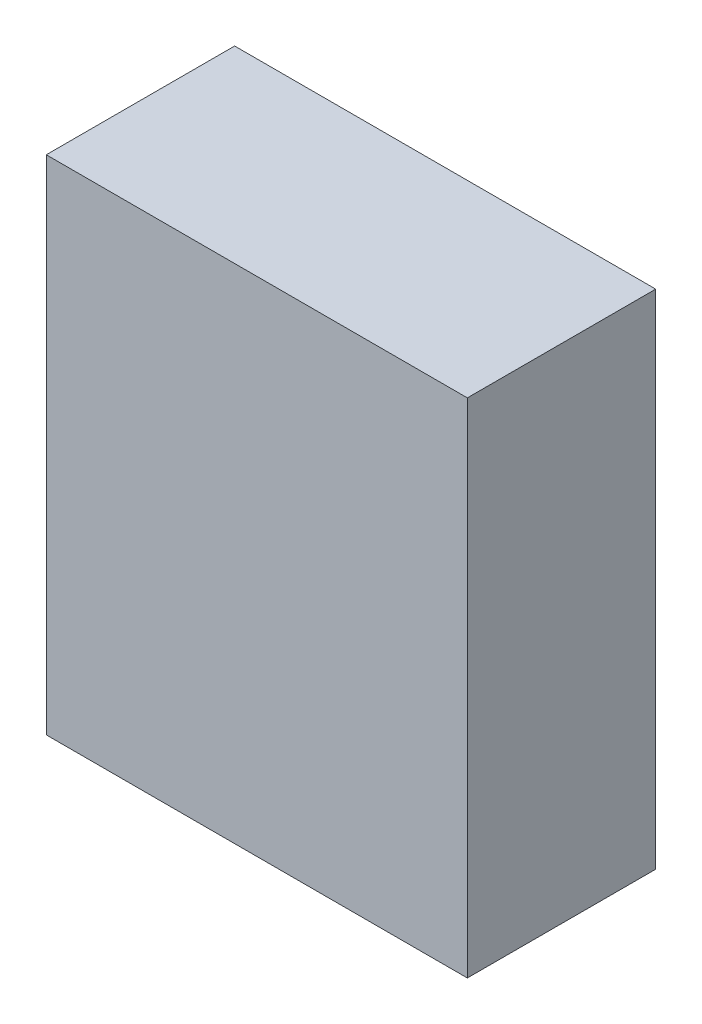
SolidWorks part; units mm, degrees
ref_plane "Front Plane" through (0, 0, 0) normal (0, 0, 1) x (1, 0, 0)
ref_plane "Top Plane" through (0, 0, 0) normal (0, 1, 0) x (1, 0, 0)
ref_plane "Right Plane" through (0, 0, 0) normal (1, 0, 0) x (0, 0, -1)
sketch "Sketch1" plane through (0, 0, 0) normal (0, 0, 1) x (1, 0, 0)
  line L0 (-1.1176, 1.2446) -> (1.1176, 1.2446)
  line L1 (1.1176, 1.2446) -> (1.1176, -1.4224)
  line L2 (1.1176, -1.4224) -> (-1.1176, -1.4224)
  line L3 (-1.1176, -1.4224) -> (-1.1176, 1.2446)
extrude "Component_Outline" add sketch "Sketch1" along normal blind 1 separate body
sketch3d "3DSketch1"
  line L0 (0, 0, 0) -> (1, 0, 0)
  line L1 (0, 0, 0) -> (0, 1, 0)
  line L2 (0, 0, 0) -> (0, 0, 1)
  point P0 (0, 0, 0)
